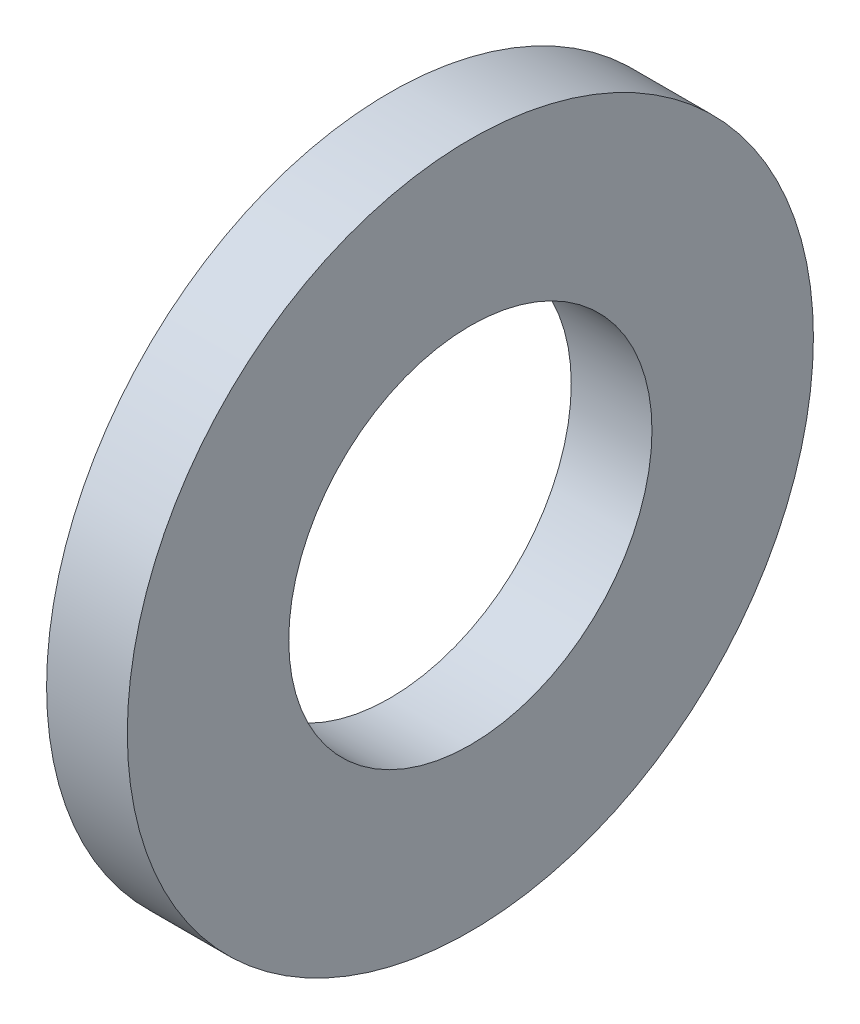
SolidWorks part; units mm, degrees
ref_plane "Plane1" through (0, 0, 0) normal (0, 0, 1) x (1, 0, 0)
ref_plane "Plane2" through (0, 0, 0) normal (0, 1, 0) x (1, 0, 0)
ref_plane "Plane3" through (0, 0, 0) normal (1, 0, 0) x (0, 0, -1)
other "Configuration Table"
sketch "Sketch1" plane through (0, 0, 0) normal (0, 0, 1) x (1, 0, 0)
  line L0 (-34.925, 0) -> (9.525, 0) construction
  line L1 (0, 9) -> (0, 17)
  line L2 (0, 17) -> (-4, 17)
  line L3 (-4, 17) -> (-4, 9)
  line L4 (-4, 9) -> (0, 9)
  dimension "Thickness" = 4
  dimension "Inside_dia" = 18
  dimension "Outside_dia" = 34
revolve "Base-Revolve" add sketch "Sketch1" angle 360 about L0
